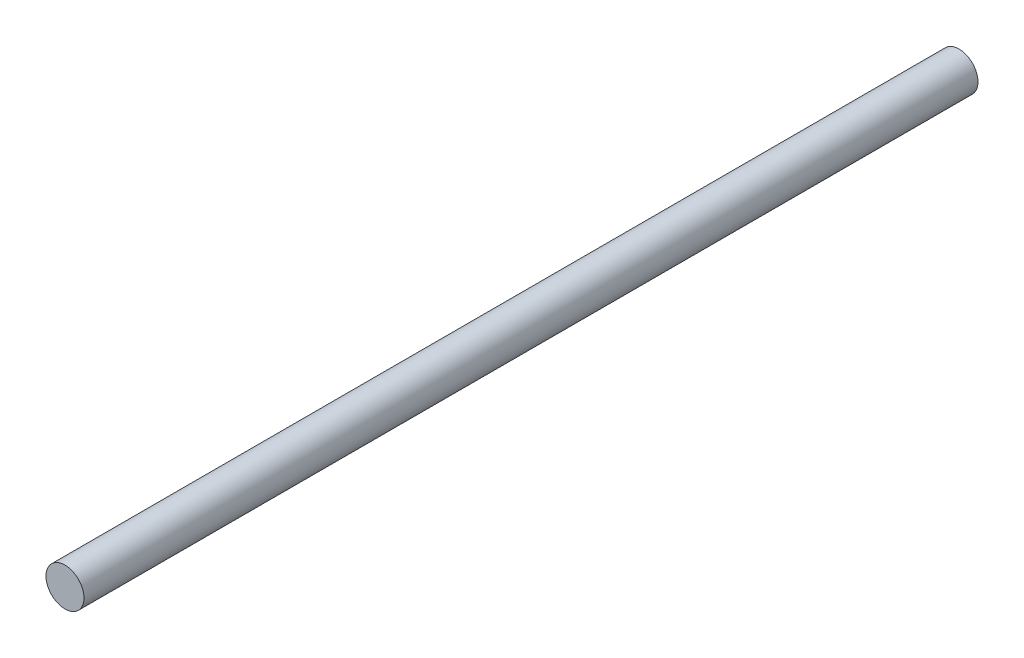
SolidWorks part; units mm, degrees
material "Plain Carbon Steel"
ref_plane "Front Plane" through (0, 0, 0) normal (0, 0, 1) x (1, 0, 0)
ref_plane "Top Plane" through (0, 0, 0) normal (0, 1, 0) x (1, 0, 0)
ref_plane "Right Plane" through (0, 0, 0) normal (1, 0, 0) x (0, 0, -1)
sketch "Sketch2" plane through (0, 0, 0) normal (0, 0, 1) x (1, 0, 0)
  circle A0 centre (0, 0) radius 12.7
  dimension "D1" = 25.4
extrude "Boss-Extrude1" add sketch "Sketch2" along normal blind 596.9
